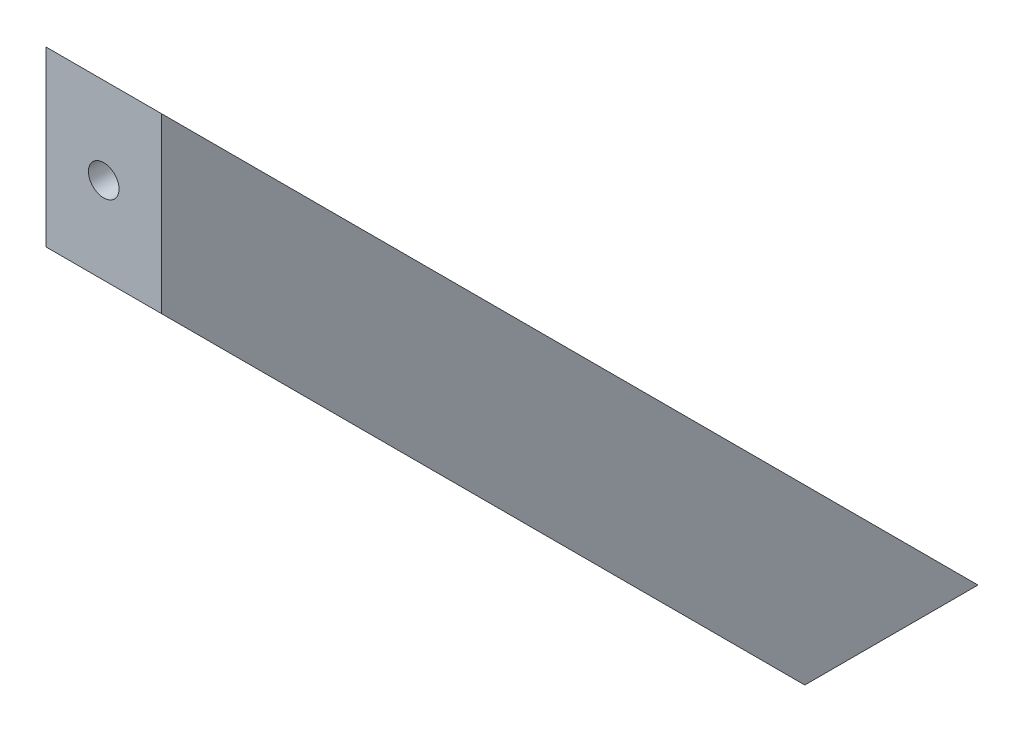
SolidWorks part; units mm, degrees
ref_plane "Front Plane" through (0, 0, 0) normal (0, 0, 1) x (1, 0, 0)
ref_plane "Top Plane" through (0, 0, 0) normal (0, 1, 0) x (1, 0, 0)
ref_plane "Right Plane" through (0, 0, 0) normal (1, 0, 0) x (0, 0, -1)
sketch "Sketch2" plane through (0, 0, 0) normal (1, 0, 0) x (0, 0, -1)
  line L6 (0, 0) -> (-111.4214, 111.4214)
  line L7 (-111.4214, 111.4214) -> (-111.4214, 141.4214)
  line L8 (-111.4214, 141.4214) -> (30, 0)
  line L9 (30, 0) -> (0, 0)
  dimension "D1" = 30
  dimension "D2" = 45
  dimension "D3" = 30
  dimension "D4" = 200
extrude "Boss-Extrude1" add sketch "Sketch2" along normal blind 20
sketch "Sketch3" plane through (0, 0, 0) normal (0, -1, 0) x (1, 0, 0)
  line L0 (10, 0) -> (10, -30) construction
  line L1 (20, 0) -> (0, 0) construction
  line L2 (20, -30) -> (0, -30) construction
  line L3 (0, -15) -> (20, -15) construction
  line L4 (0, 0) -> (0, -30) construction
  line L5 (20, 0) -> (20, -30) construction
  circle A0 centre (10, -15) radius 2.65
  dimension "D1" = 5.3
extrude "Cut-Extrude1" cut sketch "Sketch3" against normal through all
sketch "Sketch4" plane through (0, 0, 111.4214) normal (0, 0, 1) x (1, 0, 0)
  line L0 (10, 141.4214) -> (10, 111.4214) construction
  line L1 (20, 141.4214) -> (0, 141.4214) construction
  line L2 (20, 111.4214) -> (0, 111.4214) construction
  line L3 (0, 126.4214) -> (20, 126.4214) construction
  line L4 (0, 141.4214) -> (0, 111.4214) construction
  line L5 (20, 141.4214) -> (20, 111.4214) construction
  circle A0 centre (10, 126.4214) radius 2.65
  dimension "D1" = 5.3
extrude "Cut-Extrude2" cut sketch "Sketch4" against normal through all
ref_plane "Plane1" through (0, 0, 106.4214) normal (0, 0, 1) x (1, 0, 0)
sketch "Sketch5" plane through (0, 0, 106.4214) normal (0, 0, 1) x (1, 0, 0)
  circle A0 centre (10, 126.4214) radius 5.5
  dimension "D1" = 11
extrude "Cut-Extrude3" cut sketch "Sketch5" against normal through all
ref_plane "Plane2" through (0, 5, 0) normal (0, -1, 0) x (-1, 0, 0)
sketch "Sketch6" plane through (0, 5, 0) normal (0, -1, 0) x (-1, 0, 0)
  circle A0 centre (-10, 15) radius 5.5
  dimension "D1" = 11
extrude "Cut-Extrude4" cut sketch "Sketch6" against normal through all
